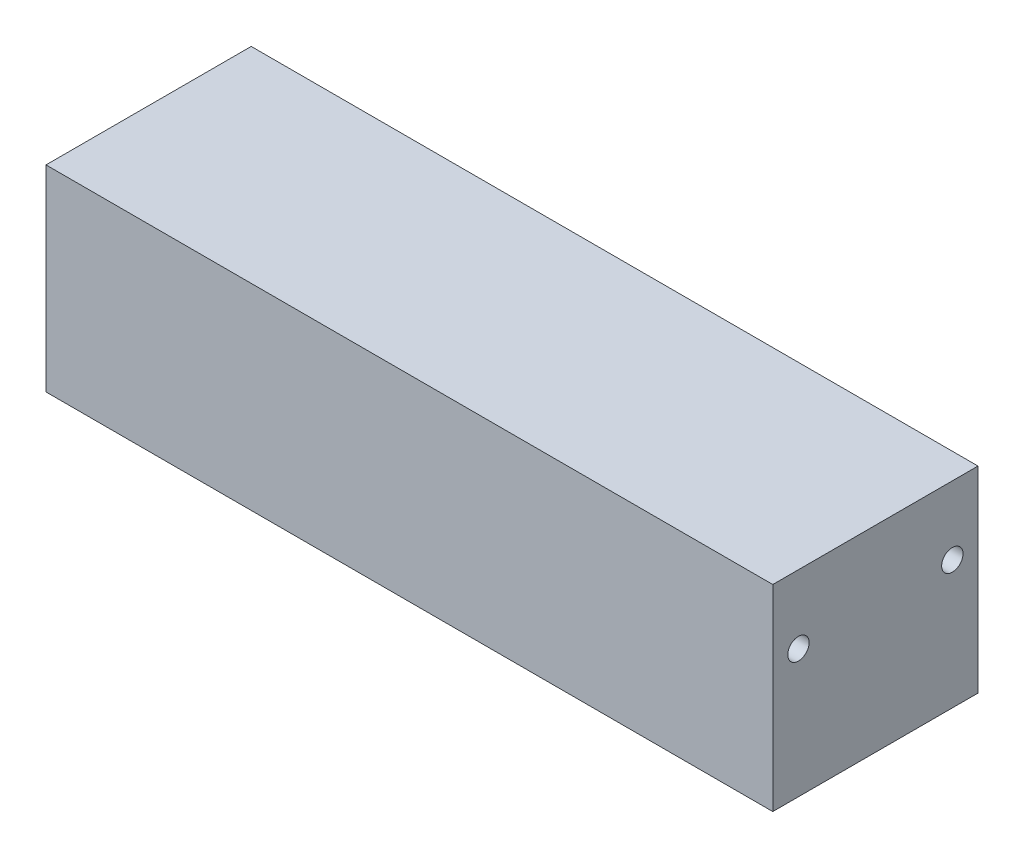
SolidWorks part; units mm, degrees
ref_plane "Front Plane" through (0, 0, 0) normal (0, 0, 1) x (1, 0, 0)
ref_plane "Top Plane" through (0, 0, 0) normal (0, 1, 0) x (1, 0, 0)
ref_plane "Right Plane" through (0, 0, 0) normal (1, 0, 0) x (0, 0, -1)
sketch "Sketch1" plane through (0, 0, 0) normal (0, 0, 1) x (1, 0, 0)
  line L1 (42.5, -11.5) -> (-42.5, -11.5)
  line L2 (42.5, -11.5) -> (42.5, 11.5)
  line L3 (42.5, 11.5) -> (-42.5, 11.5)
  line L4 (-42.5, -11.5) -> (-42.5, 11.5)
  line L5 (42.5, -11.5) -> (-42.5, 11.5) construction
  line L6 (42.5, 11.5) -> (-42.5, -11.5) construction
  point P0 (0, 0)
  dimension "D1" = 23
  dimension "D2" = 85
extrude "Boss-Extrude1" add sketch "Sketch1" along normal blind 24
sketch "Sketch3" plane through (0, -11.5, 0) normal (0, -1, 0) x (1, 0, 0)
  line L0 (-42.5, 12) -> (42.5, 12) construction
  line L1 (-42.5, 24) -> (-42.5, 0) construction
  line L2 (42.5, 24) -> (42.5, 0) construction
  circle A0 centre (-25, 12) radius 1.25
  circle A1 centre (25, 12) radius 1.25
  dimension "D3" = 2.5
  dimension "D1" = 50
  dimension "D2" = 25
extrude "Cut-Extrude1" cut sketch "Sketch3" against normal blind 4
sketch "Sketch4" plane through (42.5, 0, 0) normal (1, 0, 0) x (0, 0, -1)
  line L0 (-12, -11.5) -> (-12, 11.5) construction
  line L1 (-24, -11.5) -> (0, -11.5) construction
  line L2 (-24, 11.5) -> (0, 11.5) construction
  circle A0 centre (-3, 3.5) radius 1.25
  circle A1 centre (-21, 3.5) radius 1.25
  dimension "D1" = 2.5
  dimension "D2" = 18
  dimension "D3" = 8
extrude "Cut-Extrude2" cut sketch "Sketch4" against normal blind 4
mirror "Mirror1" about plane through (0, 0, 0) normal (1, 0, 0) of "Cut-Extrude2"
sketch "Sketch5" plane through (0, -11.5, 0) normal (0, -1, 0) x (1, 0, 0)
  line L0 (-42.5, 12) -> (42.5, 12) construction
  line L1 (-42.5, 24) -> (-42.5, 0) construction
  line L2 (42.5, 24) -> (42.5, 0) construction
  circle A0 centre (-34.5, 12) radius 2
  dimension "D2" = 4
  dimension "D1" = 8
extrude "Boss-Extrude3" add sketch "Sketch5" along normal blind 10
